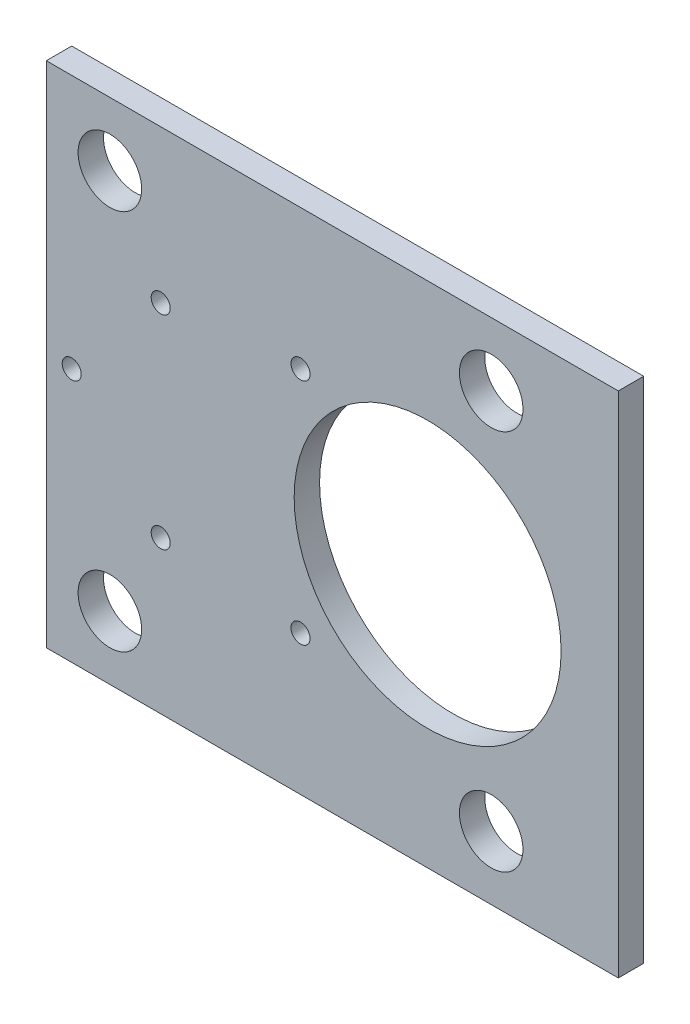
SolidWorks part; units mm, degrees
ref_plane "前视基准面" through (0, 0, 0) normal (0, 0, 1) x (1, 0, 0)
ref_plane "上视基准面" through (0, 0, 0) normal (0, 1, 0) x (1, 0, 0)
ref_plane "右视基准面" through (0, 0, 0) normal (1, 0, 0) x (0, 0, -1)
sketch "草图1" plane through (0, 0, 0) normal (0, 0, 1) x (1, 0, 0)
  line L1 (-20, -20) -> (20, -20)
  line L2 (-20, -20) -> (-20, 20)
  line L3 (-20, 20) -> (20, 20)
  line L5 (-20, -20) -> (20, 20) construction
  line L6 (-20, 20) -> (20, -20) construction
  line L7 (20, -10) -> (-20, -10) construction
  line L9 (20, 10) -> (-20, 10) construction
  line L10 (-20, -10) -> (-20, 10) construction
  line L11 (20, -10) -> (-20, 10) construction
  line L12 (20, 10) -> (-20, -10) construction
  line L13 (20, 20) -> (25, 20)
  line L15 (20, -20) -> (25, -20)
  line L16 (25, 20) -> (25, -20)
  circle A0 centre (-15, 15) radius 2.5
  circle A1 centre (15, 15) radius 2.5
  circle A2 centre (-15, -15) radius 2.5
  circle A3 centre (15, -15) radius 2.5
  circle A4 centre (-18, 0) radius 0.75
  circle A5 centre (-11, 8) radius 0.75
  circle A6 centre (0, 9) radius 0.75
  circle A7 centre (-11, -8) radius 0.75
  circle A8 centre (0, -9) radius 0.75
  circle A9 centre (10, 0) radius 10.5
  point P0 (0, 0)
  point P24 (0, 0)
  dimension "D3" = 5
  dimension "D4" = 5
  dimension "D5" = 5
  dimension "D12" = 5
  dimension "D15" = 20
  dimension "D16" = 1.5
  dimension "D17" = 1.5
  dimension "D18" = 1.5
  dimension "D19" = 1.5
  dimension "D20" = 1.5
  dimension "D30" = 21
  dimension "D1" = 40
  dimension "D2" = 40
  dimension "D6" = 5
  dimension "D7" = 5
  dimension "D8" = 5
  dimension "D11" = 5
  dimension "D13" = 5
  dimension "D14" = 5
  dimension "D21" = 2
  dimension "D22" = 9
  dimension "D23" = 9
  dimension "D24" = 2
  dimension "D25" = 2
  dimension "D26" = 1
  dimension "D27" = 1
  dimension "D28" = 20
  dimension "D29" = 20
  dimension "D32" = 5
extrude "凸台-拉伸1" add sketch "草图1" along normal blind 2
